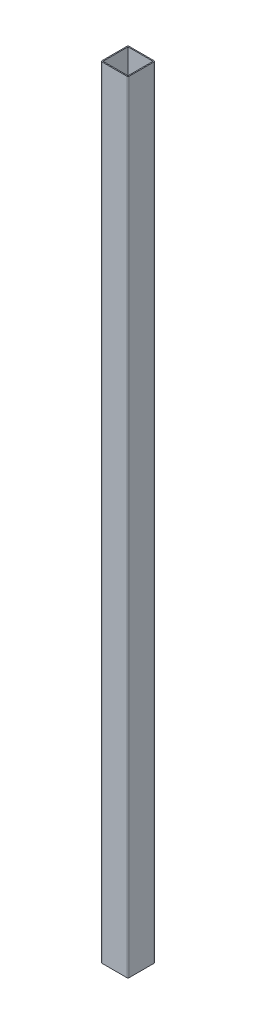
SolidWorks part; units mm, degrees
material "Простая углеродистая сталь"
ref_plane "Спереди" through (0, 0, 0) normal (0, 0, 1) x (1, 0, 0)
ref_plane "Сверху" through (0, 0, 0) normal (0, 1, 0) x (1, 0, 0)
ref_plane "Справа" through (0, 0, 0) normal (1, 0, 0) x (0, 0, -1)
sketch "Эскиз1" plane through (0, 0, 0) normal (0, 0, 1) x (1, 0, 0)
  line L0 (0, 0) -> (0, -4614)
  dimension "D1" = 4614
other "Квадратная труба гост 8639-82 150 X 150 X 7.0(1)"
ref_plane "Плоскость1" through (0, 0, 0) normal (0, -1, 0) x (1, 0, 0)
sketch "Sketch1" plane through (0, 0, 0) normal (0, -1, 0) x (1, 0, 0)
  line L0 (-73.999, -74) -> (73.999, -74)
  line L1 (-74, -73.999) -> (-74, 73.999)
  line L2 (73.999, 74) -> (-73.999, 74)
  line L3 (74, 73.999) -> (74, -73.999)
  line L4 (-73.999, -80) -> (73.999, -80)
  line L5 (-80, -73.999) -> (-80, 73.999)
  line L6 (73.999, 80) -> (-73.999, 80)
  line L7 (80, 73.999) -> (80, -73.999)
  arc A0 (80, 73.999) -> (73.999, 80) centre (73.999, 73.999) ccw
  arc A1 (73.999, -80) -> (80, -73.999) centre (73.999, -73.999) ccw
  arc A2 (-80, -73.999) -> (-73.999, -80) centre (-73.999, -73.999) ccw
  arc A3 (-73.999, 80) -> (-80, 73.999) centre (-73.999, 73.999) ccw
  arc A4 (-73.999, 74) -> (-74, 73.999) centre (-73.999, 73.999) ccw
  arc A5 (74, 73.999) -> (73.999, 74) centre (73.999, 73.999) ccw
  arc A6 (73.999, -74) -> (74, -73.999) centre (73.999, -73.999) ccw
  arc A7 (-74, -73.999) -> (-73.999, -74) centre (-73.999, -73.999) ccw
  point P0 (-80, 0)
  point P1 (80, 0)
  point P2 (0, 80)
  point P3 (0, -80)
  point P4 (0, 0)
  point P5 (-80, -80)
  point P6 (80, -80)
  point P7 (80, 80)
  point P8 (-80, 80)
  point P33 (0, 0)
  dimension "D1" = 6.001
  dimension "Thickness" = 6
  dimension "V_leg" = 160
sketch "Эскиз3" plane through (0, 0, 80) normal (0, 0, 1) x (1, 0, 0)
  line L0 (-80, 0) -> (80, -20)
  line L1 (80, -4614) -> (80, 0) construction
  line L2 (80, -20) -> (80, 0)
  line L3 (80, 0) -> (-80, 0)
  dimension "D1" = 20
extrude "Вырез-Вытянуть1" [suppressed] cut sketch "Эскиз3" against normal up to vertex
equation "\"D1@Sketch1\" = \"Thickness@Sketch1\"+0.001"
